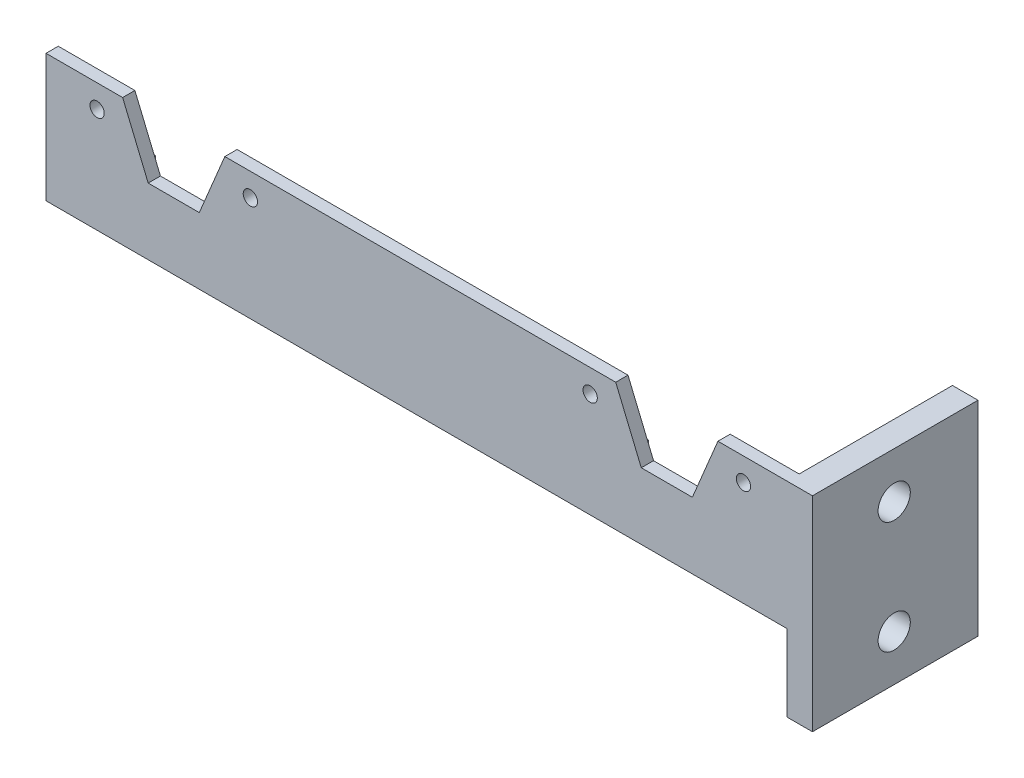
SolidWorks part; units mm, degrees
ref_plane "Front Plane" through (0, 0, 0) normal (0, 0, 1) x (1, 0, 0)
ref_plane "Top Plane" through (0, 0, 0) normal (0, 1, 0) x (1, 0, 0)
ref_plane "Right Plane" through (0, 0, 0) normal (1, 0, 0) x (0, 0, -1)
sketch "Sketch1" plane through (0, 0, 0) normal (0, 0, 1) x (1, 0, 0)
  line L1 (0, 0) -> (150, 0)
  line L2 (0, 0) -> (0, 25)
  line L3 (0, 25) -> (150, 25)
  line L4 (150, 0) -> (150, 25)
  dimension "D1" = 150
  dimension "D2" = 25
extrude "Boss-Extrude1" add sketch "Sketch1" along normal blind 2.4
sketch "Sketch2" plane through (0, 0, 2.4) normal (0, 0, 1) x (1, 0, 0)
  line L0 (25, 25) -> (25, 0) construction
  line L1 (150, 25) -> (0, 25) construction
  line L2 (0, 0) -> (150, 0) construction
  line L3 (121.5, 25) -> (121.5, 0) construction
  line L4 (150, 0) -> (150, 25) construction
  line L5 (131.5, 25) -> (126.5, 13)
  line L6 (126.5, 13) -> (116.5, 13)
  line L7 (111.5, 25) -> (116.5, 13)
  line L8 (35, 25) -> (30, 13)
  line L9 (30, 13) -> (20, 13)
  line L10 (15, 25) -> (20, 13)
  line L11 (15, 25) -> (35, 25)
  line L12 (111.5, 25) -> (131.5, 25)
  line L13 (0, 20.5) -> (150, 20.5) construction
  line L14 (0, 25) -> (0, 0) construction
  line L15 (73.25, 25) -> (73.25, 0) construction
  circle A0 centre (40, 20.5) radius 1.4
  circle A1 centre (10, 20.5) radius 1.4
  circle A2 centre (106.5, 20.5) radius 1.4
  circle A3 centre (136.5, 20.5) radius 1.4
  point P14 (121.5, 13)
  point P19 (25, 13)
  dimension "D10" = 2.8
  dimension "D1" = 28.5
  dimension "D2" = 125
  dimension "D3" = 5
  dimension "D4" = 10
  dimension "D5" = 5
  dimension "D6" = 10
  dimension "D7" = 12
  dimension "D8" = 12
  dimension "D9" = 7.5
  dimension "D11" = 15
  dimension "D12" = 48.25
extrude "Cut-Extrude1" cut sketch "Sketch2" against normal through all
sketch "Sketch3" plane through (0, 0, 0) normal (0, 0, -1) x (-1, 0, 0)
  line L1 (-150, 25) -> (-145, 25)
  line L2 (-150, 25) -> (-150, -15)
  line L3 (-150, -15) -> (-145, -15)
  line L4 (-145, 25) -> (-145, -15)
  line L5 (-150, 25) -> (-131.5, 25) construction
  line L6 (0, 0) -> (-150, 0) construction
  dimension "D1" = 5
  dimension "D2" = 40
extrude "Boss-Extrude2" add sketch "Sketch3" along normal blind 30 and the other way up to surface other way up to face at (137.9, 20.5, 2.4)
sketch "Sketch4" plane through (145, 0, 0) normal (-1, 0, 0) x (0, 0, 1)
  line L0 (-13.6, 25) -> (-13.6, -15) construction
  line L1 (-30, 25) -> (0, 25) construction
  line L2 (-30, -15) -> (2.4, -15) construction
  line L3 (2.4, -15) -> (2.4, 25) construction
  circle A0 centre (-13.6, 16) radius 3.15
  circle A1 centre (-13.6, -6) radius 3.15
  dimension "D2" = 6.3
  dimension "D4" = 6.3
  dimension "D1" = 16
  dimension "D3" = 9
  dimension "D5" = 9
extrude "Cut-Extrude2" cut sketch "Sketch4" against normal blind 30
sketch "Sketch6" plane through (0, 0, 0) normal (0, -1, 0) x (1, 0, 0)
  line L0 (145, -30) -> (145, 2.4) construction
  line L1 (0, 0) -> (145, 0)
  line L2 (0, 0) -> (0, -2)
  line L3 (0, -2) -> (145, -2)
  line L4 (145, 0) -> (145, -2)
  dimension "D1" = 2
extrude "Boss-Extrude3" [suppressed] add sketch "Sketch6" against normal up to surface (15 mm away)
sketch "Sketch7" [suppressed] plane through (0, 0, 0) normal (-1, 0, 0) x (0, 0, 1)
  line L0 (-2, 0) -> (0, 15)
  line L1 (0, 15) -> (-5.2606, 15)
  line L2 (-5.2606, 15) -> (-2, 0)
extrude "Cut-Extrude3" [suppressed] cut sketch "Sketch7" against normal up to surface (144 mm away)
chamfer "Chamfer2" [suppressed] distance 2 angle 45
fillet "Fillet2" [suppressed] radius 2
chamfer "Chamfer3" [suppressed] distance 3 angle 15
chamfer "Chamfer4" [suppressed] distance 2 angle 79
sketch "Sketch8" plane through (145, 0, 0) normal (-1, 0, 0) x (0, 0, 1)
  line L0 (-30, 5) -> (0, 5) construction
  line L1 (-30, -15) -> (-30, 25) construction
  line L2 (0, 0) -> (0, 25) construction
  line L4 (-10, 4) -> (0, 4)
  line L5 (-10, 4) -> (-10, 6)
  line L6 (-10, 6) -> (0, 6)
  line L7 (0, 4) -> (0, 6)
  line L8 (-10, 4) -> (0, 6) construction
  line L9 (-10, 6) -> (0, 4) construction
  point P6 (-5, 5)
  dimension "D1" = 2
  dimension "D2" = 10
extrude "Boss-Extrude4" add sketch "Sketch8" along normal up to surface (145 mm away) up to face at (0, 12.5, 1.2)
sketch "Sketch9" plane through (0, 25, 0) normal (0, 1, 0) x (1, 0, 0)
  line L0 (131.5, 0) -> (131.5, 12.5409)
  line L1 (131.5, 12.5409) -> (111.5, 12.5409)
  line L2 (111.5, 12.5409) -> (111.5, 0)
  line L3 (111.5, 0) -> (131.5, 0)
  line L4 (35, 0) -> (35, 13.0069)
  line L5 (35, 13.0069) -> (15, 13.0069)
  line L6 (15, 13.0069) -> (15, 0)
  line L7 (15, 0) -> (35, 0)
extrude "Cut-Extrude4" cut sketch "Sketch9" against normal through all
chamfer "Chamfer5" distance 6 angle 45 5 edges at (111.5, 5, -10) (15, 5, -10) (0, 5, -10) (35, 5, -10) (131.5, 5, -10)
